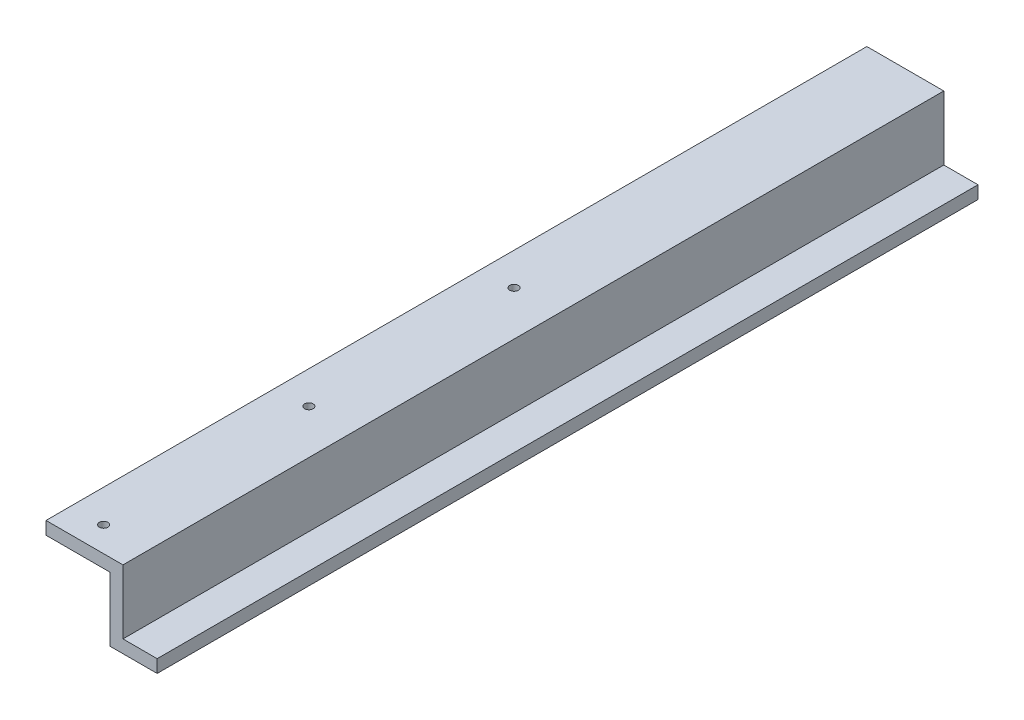
SolidWorks part; units mm, degrees
ref_plane "Front Plane" through (0, 0, 0) normal (0, 0, 1) x (1, 0, 0)
ref_plane "Top Plane" through (0, 0, 0) normal (0, 1, 0) x (1, 0, 0)
ref_plane "Right Plane" through (0, 0, 0) normal (1, 0, 0) x (0, 0, -1)
sketch "Sketch1" plane through (0, 0, 0) normal (0, 0, 1) x (1, 0, 0)
  line L0 (0, -11.9062) -> (0, 11.9062) construction
  line L1 (0, 11.9062) -> (-26.1938, 11.9062) construction
  line L2 (0, -11.9062) -> (26.1938, -11.9062) construction
  line L3 (2.3812, -9.525) -> (26.1938, -9.525) construction
  line L4 (2.3812, -9.525) -> (2.3812, 14.2875) construction
  line L5 (2.3812, 14.2875) -> (-26.1938, 14.2875) construction
  line L6 (-2.3812, -14.2875) -> (26.1938, -14.2875) construction
  line L7 (-2.3812, -14.2875) -> (-2.3812, 9.525) construction
  line L8 (-2.3812, 9.525) -> (-26.1938, 9.525) construction
  line L9 (-26.1938, 14.2875) -> (-26.1938, 9.525) construction
  line L10 (26.1938, -9.525) -> (26.1938, -14.2875) construction
  point P4 (0, 0)
  dimension "Leg Width" = 28.575
  dimension "Outside Height" = 28.575
  dimension "Wall Thickness" = 4.7625
sketch "Sketch2" plane through (0, 0, 0) normal (1, 0, 0) x (0, 0, -1)
  line L0 (152.4, 0) -> (-152.4, 0) construction
  line L1 (0, 0) -> (0, 14.2875) construction
  line L2 (-152.4, 0) -> (-152.4, 14.2875) construction
  line L3 (152.4, 0) -> (152.4, 14.2875) construction
  point P0 (-114.3, 0)
  point P3 (114.3, 0)
  point P4 (0, 0)
  dimension "D1" = 228.6
  dimension "Length" = 304.8
sketch "Sketch3" plane through (0, 0, 0) normal (0, 0, 1) x (1, 0, 0)
  line L1 (2.3812, -9.525) -> (26.1938, -9.525) construction
  line L2 (-2.3812, -14.2875) -> (26.1938, -14.2875) construction
  line L3 (-2.3812, -14.2875) -> (-2.3812, 9.525) construction
  line L4 (2.3812, -9.525) -> (2.3812, 14.2875) construction
  line L5 (2.3812, 14.2875) -> (-26.1938, 14.2875) construction
  line L6 (-26.1938, 14.2875) -> (-26.1938, 9.525) construction
  line L7 (-2.3812, 9.525) -> (-26.1938, 9.525) construction
  line L8 (15.0812, -9.525) -> (15.0812, -14.2875)
  line L9 (2.3812, -9.525) -> (15.0812, -9.525)
  line L10 (-2.3812, -14.2875) -> (15.0812, -14.2875)
  line L11 (-2.3812, -14.2875) -> (-2.3812, 9.525)
  line L12 (2.3812, -9.525) -> (2.3812, 14.2875)
  line L13 (2.3812, 14.2875) -> (-26.1938, 14.2875)
  line L14 (-26.1938, 14.2875) -> (-26.1938, 9.525)
  line L15 (-2.3812, 9.525) -> (-26.1938, 9.525)
  dimension "D1" = 17.4625
extrude "Boss-Extrude1" add sketch "Sketch3" along normal up to vertex (152.4 mm away) and the other way up to vertex (152.4 mm away) up to point (0, 0, 152.4) other way up to point (0, 0, -152.4)
sketch "Sketch6" plane through (0, 9.525, 0) normal (0, -1, 0) x (1, 0, 0)
  line L0 (-26.1938, 152.4) -> (-2.3812, 152.4) construction
  line L1 (-26.1938, 152.4) -> (-26.1938, -152.4) construction
  line L2 (-2.3812, 152.4) -> (-2.3812, -152.4) construction
  circle A3 centre (-14.0958, 143.0942) radius 1.5875
  circle A5 centre (-14.0958, 66.8942) radius 1.5875
  circle A6 centre (-14.0958, -9.3058) radius 1.5875
  dimension "D1" = 76.2
  dimension "D3" = 9.3058
  dimension "D5" = 3.175
  dimension "D6" = 3.175
  dimension "D7" = 3.175
  dimension "D2" = 76.2
  dimension "D4" = 12.0979
  dimension "D8" = 11.7146
extrude "Cut-Extrude1" cut sketch "Sketch6" against normal blind 4.7625 contours A3 | A5 | A6
sketch "Sketch8" [suppressed] plane through (0, 14.2875, 0) normal (0, 1, 0) x (1, 0, 0)
  line L0 (2.3812, 152.4) -> (-26.1938, 152.4) construction
  line L1 (15.0812, 57.6) -> (-26.1938, 57.6)
  line L2 (15.0812, 57.6) -> (15.0812, 152.4)
  line L3 (15.0812, 152.4) -> (-26.1938, 152.4)
  line L4 (-26.1938, 57.6) -> (-26.1938, 152.4)
  line L5 (15.0812, 57.6) -> (-26.1938, 152.4) construction
  line L6 (15.0812, 152.4) -> (-26.1938, 57.6) construction
  line L7 (-26.1938, -152.4) -> (-26.1938, 152.4) construction
  line L8 (15.0812, -152.4) -> (15.0812, 152.4) construction
  line L9 (2.3812, -152.4) -> (-26.1938, -152.4) construction
  dimension "D1" = 210
extrude "Cut-Extrude2" [suppressed] cut sketch "Sketch8" against normal through all
equation "\"D1@Sketch2\"=\"Length@Sketch2\"*0.75"
